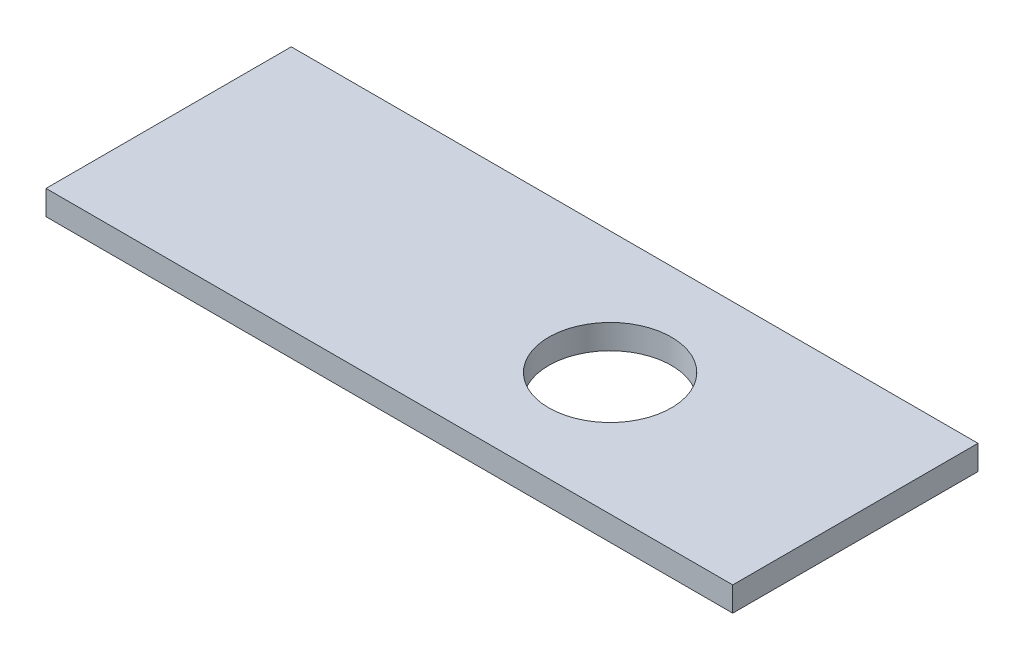
SolidWorks part; units mm, degrees
ref_plane "前视基准面" through (0, 0, 0) normal (0, 0, 1) x (1, 0, 0)
ref_plane "上视基准面" through (0, 0, 0) normal (0, 1, 0) x (1, 0, 0)
ref_plane "右视基准面" through (0, 0, 0) normal (1, 0, 0) x (0, 0, -1)
sketch "草图1" plane through (0, 0, 0) normal (0, 1, 0) x (1, 0, 0)
  line L1 (8, 5) -> (-20, 5)
  line L2 (8, 5) -> (8, -5)
  line L3 (8, -5) -> (-20, -5)
  line L4 (-20, 5) -> (-20, -5)
  circle A0 centre (-2, 0) radius 2.5
  point P0 (0, 0)
  dimension "D3" = 10
  dimension "D1" = 28
  dimension "D2" = 10
extrude "凸台-拉伸1" add sketch "草图1" along normal blind 1
